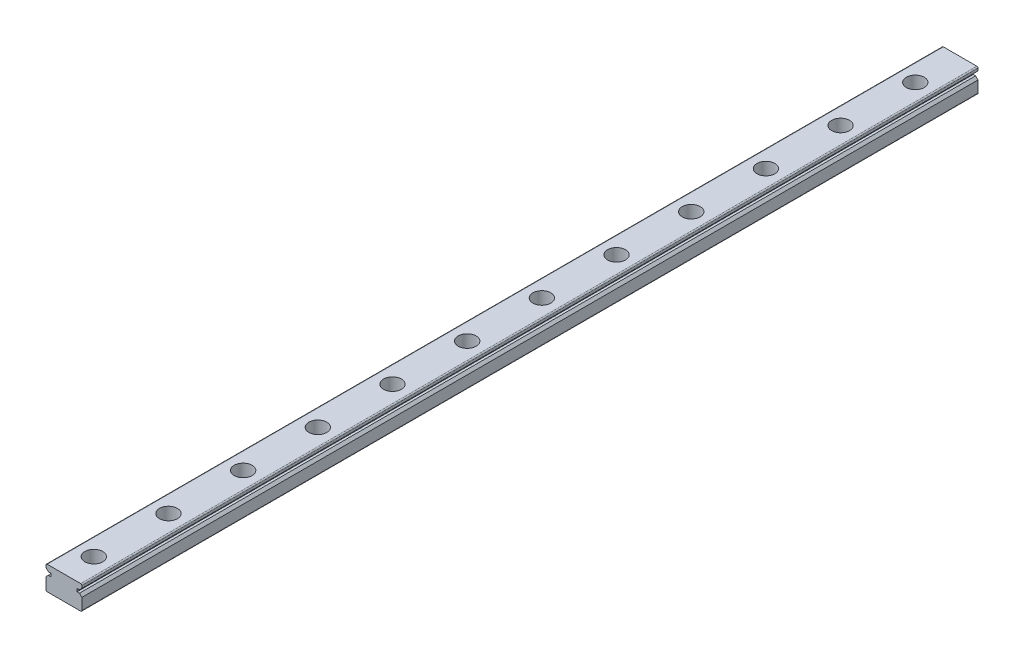
SolidWorks part; units mm, degrees
ref_plane "Front Plane" through (0, 0, 0) normal (0, 0, 1) x (1, 0, 0)
ref_plane "Top Plane" through (0, 0, 0) normal (0, 1, 0) x (1, 0, 0)
ref_plane "Right Plane" through (0, 0, 0) normal (1, 0, 0) x (0, 0, -1)
sketch "Sketch1" plane through (0, 0, 0) normal (0, 0, 1) x (1, 0, 0)
  line L0 (0, -1000) -> (0, 1.5) construction
  line L1 (-5.6, 4) -> (5.6, 4)
  line L2 (-6, 3.6) -> (-6, 2.8)
  line L3 (-5.6, -4) -> (5.6, -4)
  line L4 (6, 3.6) -> (6, 2.8)
  line L5 (-6, 4) -> (6, -4) construction
  line L6 (-6, -4) -> (6, 4) construction
  line L7 (6, 0.2) -> (6, -3.6)
  line L8 (-5.2, 2) -> (-4.4, 2)
  line L9 (-4.4, 2) -> (-4.4, 1)
  line L10 (-5.2, 1) -> (-4.4, 1)
  line L11 (4.4, 2) -> (4.4, 1)
  line L14 (-6, 0.2) -> (-6, -3.6)
  line L15 (4.4, 2) -> (5.2, 2)
  line L16 (4.4, 1) -> (5.2, 1)
  line L17 (0, 1.5) -> (0, 1001.8645) construction
  line L18 (-6, 2.8) -> (-5.2, 2)
  line L19 (-6, 0.2) -> (-5.2, 1)
  line L20 (5.2, 2) -> (6, 2.8)
  line L21 (5.2, 1) -> (6, 0.2)
  arc A0 (-6, -3.6) -> (-5.6, -4) centre (-5.6, -3.6) ccw
  arc A1 (5.6, -4) -> (6, -3.6) centre (5.6, -3.6) ccw
  arc A2 (5.6, 4) -> (6, 3.6) centre (5.6, 3.6) cw
  arc A3 (-5.6, 4) -> (-6, 3.6) centre (-5.6, 3.6) ccw
  point P0 (0, 0)
  point P13 (-6, 2)
  point P14 (6, 2)
  point P15 (6, 1)
  point P16 (-6, 1)
  dimension "D5" = 0.4
  dimension "D1" = 12
  dimension "D2" = 8
  dimension "D3" = 8.8
  dimension "D4" = 5
  dimension "D6" = 2
  dimension "D7" = 5
  dimension "D8" = 4.4
extrude "Boss-Extrude1" add sketch "Sketch1" along normal blind 300
sketch "Sketch2" plane through (0, 4, 0) normal (0, 1, 0) x (1, 0, 0)
  line L0 (5.6, -300) -> (-5.6, -300) construction
  circle A0 centre (0, -290) radius 3
  circle A1 centre (0, -265) radius 3
  circle A2 centre (0, -240) radius 3
  circle A3 centre (0, -215) radius 3
  circle A4 centre (0, -190) radius 3
  circle A5 centre (0, -165) radius 3
  circle A6 centre (0, -140) radius 3
  circle A7 centre (0, -115) radius 3
  circle A8 centre (0, -90) radius 3
  circle A9 centre (0, -65) radius 3
  circle A10 centre (0, -40) radius 3
  circle A11 centre (0, -15) radius 3
  circle A12 centre (0, 10) radius 3
  circle A13 centre (0, 35) radius 3
  circle A14 centre (0, 60) radius 3
  circle A15 centre (0, 85) radius 3
  circle A16 centre (0, 110) radius 3
  circle A17 centre (0, 135) radius 3
  point P39 (0, -300)
  dimension "D1" = 10
  dimension "D2" = 6
  dimension "D3" = 18
extrude "Cut-Extrude1" cut sketch "Sketch2" against normal blind 4.5
sketch "Sketch3" plane through (0, 4, 0) normal (0, 1, 0) x (1, 0, 0)
  line L0 (5.6, -300) -> (-5.6, -300) construction
  circle A2 centre (0, -290.0015) radius 1.75
  circle A3 centre (0, -265.0015) radius 1.75
  circle A4 centre (0, -240.0015) radius 1.75
  circle A5 centre (0, -215.0015) radius 1.75
  circle A6 centre (0, -190.0015) radius 1.75
  circle A7 centre (0, -165.0015) radius 1.75
  circle A8 centre (0, -140.0015) radius 1.75
  circle A9 centre (0, -115.0015) radius 1.75
  circle A10 centre (0, -90.0015) radius 1.75
  circle A11 centre (0, -65.0015) radius 1.75
  circle A12 centre (0, -40.0015) radius 1.75
  circle A13 centre (0, -15.0015) radius 1.75
  circle A14 centre (0, 9.9985) radius 1.75
  circle A15 centre (0, 34.9985) radius 1.75
  circle A16 centre (0, 59.9985) radius 1.75
  point P6 (0, -300)
  dimension "D1" = 3.5
  dimension "D2" = 9.9985
  dimension "D3" = 15
extrude "Cut-Extrude2" cut sketch "Sketch3" against normal through all
